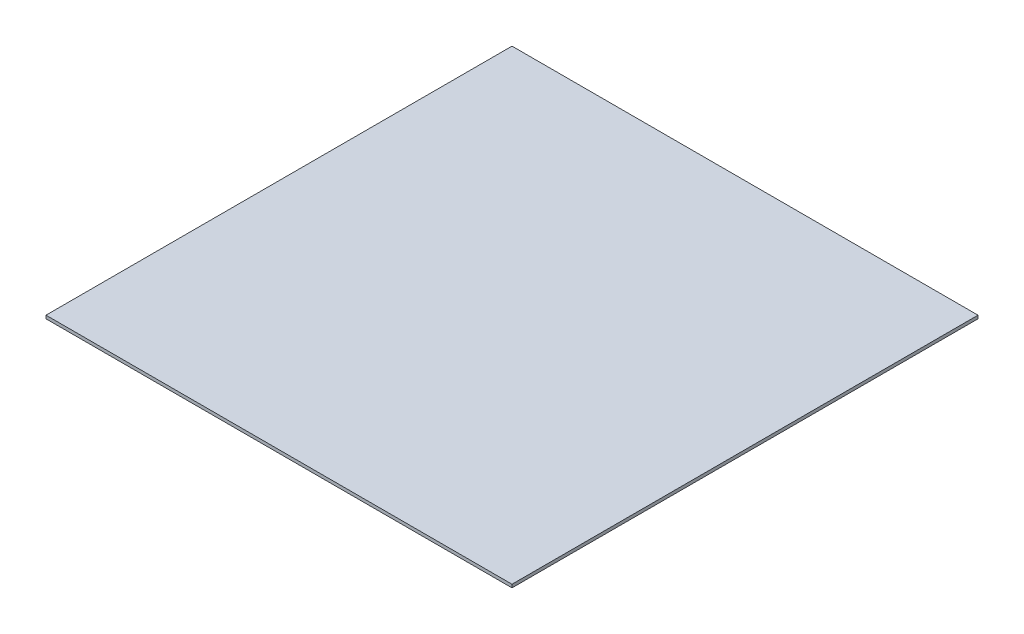
SolidWorks part; units mm, degrees
ref_plane "Front Plane" through (0, 0, 0) normal (0, 0, 1) x (1, 0, 0)
ref_plane "Top Plane" through (0, 0, 0) normal (0, 1, 0) x (1, 0, 0)
ref_plane "Right Plane" through (0, 0, 0) normal (1, 0, 0) x (0, 0, -1)
sketch "Sketch1" plane through (0, 0, 0) normal (0, 1, 0) x (1, 0, 0)
  line L1 (-11, -11) -> (11, -11)
  line L2 (-11, -11) -> (-11, 11)
  line L3 (-11, 11) -> (11, 11)
  line L4 (11, -11) -> (11, 11)
  line L5 (-11, -11) -> (11, 11) construction
  line L6 (-11, 11) -> (11, -11) construction
  point P0 (0, 0)
  dimension "D1" = 22
  dimension "D2" = 22
extrude "Boss-Extrude1" add sketch "Sketch1" along normal blind 0.15
